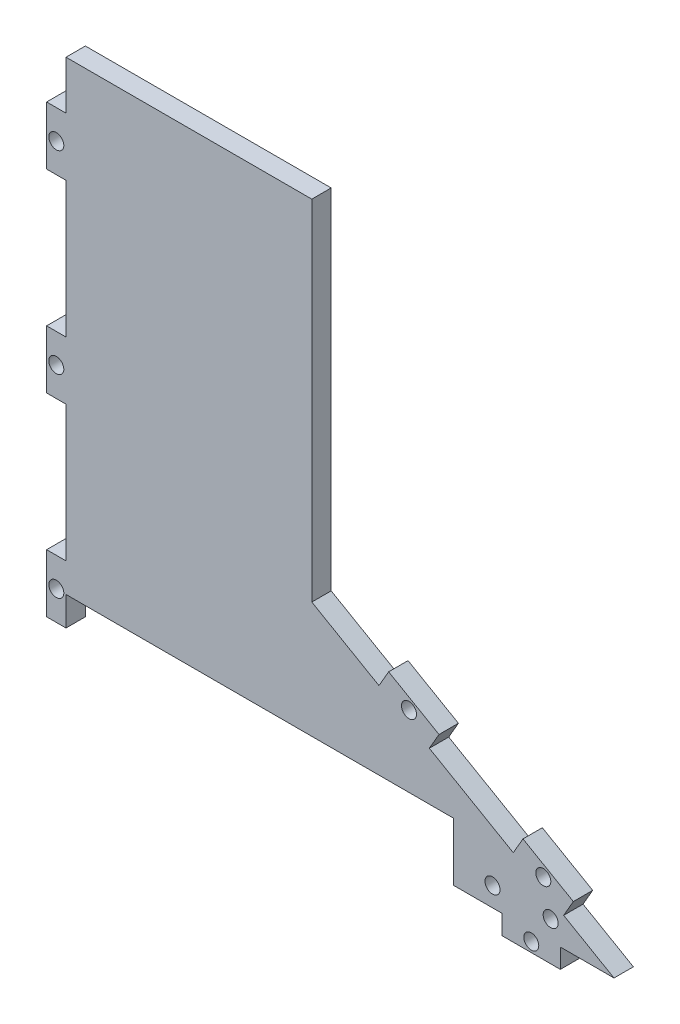
SolidWorks part; units mm, degrees
ref_plane "Front Plane" through (0, 0, 0) normal (0, 0, 1) x (1, 0, 0)
ref_plane "Top Plane" through (0, 0, 0) normal (0, 1, 0) x (1, 0, 0)
ref_plane "Right Plane" through (0, 0, 0) normal (1, 0, 0) x (0, 0, -1)
sketch "Sketch1" plane through (0, 0, 0) normal (0, 0, 1) x (1, 0, 0)
  line L0 (86.8648, 57.15) -> (185.8515, 0)
  line L1 (0, 0) -> (86.8648, 0)
  line L2 (0, 0) -> (0, 57.15)
  line L3 (0, 57.15) -> (86.8648, 57.15)
  line L5 (185.8515, 0) -> (86.8648, 0)
  dimension "D1" = 86.8648
  dimension "D2" = 30
  dimension "D3" = 114.3
extrude "Boss-Extrude1" add sketch "Sketch1" along normal blind 6.35
sketch "Sketch2" plane through (0, 0, 6.35) normal (0, 0, 1) x (1, 0, 0)
  line L0 (0, 0) -> (185.8515, 0) construction
  line L1 (6.35, 0) -> (133.35, 0)
  line L2 (6.35, 0) -> (6.35, 19.05)
  line L3 (6.35, 19.05) -> (133.35, 19.05)
  line L4 (133.35, 0) -> (133.35, 19.05)
  line L5 (0, 57.15) -> (0, 0) construction
  dimension "D1" = 127
  dimension "D2" = 19.05
  dimension "D3" = 6.35
extrude "Cut-Extrude1" cut sketch "Sketch2" against normal through all
sketch "Sketch3" plane through (0, 0, 6.35) normal (0, 0, 1) x (1, 0, 0)
  line L0 (86.8648, 57.15) -> (0, 57.15) construction
  line L1 (0, 57.15) -> (86.8648, 57.15)
  line L2 (0, 57.15) -> (0, 171.45)
  line L3 (0, 171.45) -> (86.8648, 171.45)
  line L4 (86.8648, 57.15) -> (86.8648, 171.45)
  line L5 (0, 57.15) -> (0, 0) construction
  dimension "D1" = 114.3
  dimension "D2" = 86.8648
extrude "Boss-Extrude2" add sketch "Sketch3" against normal blind 6.35
sketch "Sketch4" plane through (0, 0, 6.35) normal (0, 0, 1) x (1, 0, 0)
  line L0 (6.35, 19.05) -> (6.35, 0) construction
  line L1 (0, 0) -> (6.35, 0)
  line L2 (0, 0) -> (0, 9.525)
  line L3 (0, 9.525) -> (6.35, 9.525)
  line L4 (6.35, 0) -> (6.35, 9.525)
  line L5 (0, 171.45) -> (0, 0) construction
  line L6 (0, 28.575) -> (6.35, 28.575)
  line L7 (0, 28.575) -> (0, 73.025)
  line L8 (0, 73.025) -> (6.35, 73.025)
  line L9 (6.35, 28.575) -> (6.35, 73.025)
  line L11 (0, 92.075) -> (6.35, 92.075)
  line L12 (0, 92.075) -> (0, 136.525)
  line L13 (0, 136.525) -> (6.35, 136.525)
  line L14 (6.35, 92.075) -> (6.35, 136.525)
  line L15 (0, 171.45) -> (6.35, 171.45)
  line L16 (0, 171.45) -> (0, 155.575)
  line L17 (0, 155.575) -> (6.35, 155.575)
  line L18 (6.35, 171.45) -> (6.35, 155.575)
  dimension "D1" = 9.525
  dimension "D2" = 19.05
  dimension "D3" = 44.45
  dimension "D4" = 6.35
  dimension "D5" = 19.05
  dimension "D6" = 44.45
  dimension "D7" = 6.35
  dimension "D8" = 19.05
  dimension "D9" = 6.35
extrude "Cut-Extrude2" cut sketch "Sketch4" against normal through all
sketch "Sketch5" plane through (0, 0, 6.35) normal (0, 0, 1) x (1, 0, 0)
  line L0 (133.35, 0) -> (185.8515, 0) construction
  line L1 (149.225, 0) -> (168.275, 0)
  line L2 (149.225, 0) -> (149.225, -6.35)
  line L3 (149.225, -6.35) -> (168.275, -6.35)
  line L4 (168.275, 0) -> (168.275, -6.35)
  line L5 (6.35, 28.575) -> (6.35, 73.025) construction
  dimension "D1" = 19.05
  dimension "D2" = 6.35
  dimension "D3" = 142.875
extrude "Boss-Extrude3" add sketch "Sketch5" against normal blind 6.35
sketch "Sketch6" plane through (0, 0, 6.35) normal (0, 0, 1) x (1, 0, 0)
  line L0 (185.8515, 0) -> (86.8648, 57.15) construction
  line L1 (108.8618, 44.45) -> (125.3596, 34.925)
  line L2 (108.8618, 44.45) -> (112.0368, 49.9493)
  line L3 (112.0368, 49.9493) -> (128.5346, 40.4243)
  line L4 (125.3596, 34.925) -> (128.5346, 40.4243)
  dimension "D1" = 19.05
  dimension "D2" = 6.35
  dimension "D3" = 25.4
extrude "Boss-Extrude4" add sketch "Sketch6" against normal blind 6.35
pattern_linear "LPattern1" count 2 spacing 50.8 along (0.866, -0.5, 0) of "Boss-Extrude4"
sketch "Sketch8" [suppressed] plane through (0, 0, 6.35) normal (0, 0, 1) x (1, 0, 0)
  line L0 (0, 0) -> (185.8515, 0) construction
  line L1 (34.925, 0) -> (53.975, 0)
  line L2 (34.925, 0) -> (34.925, -6.35)
  line L3 (34.925, -6.35) -> (53.975, -6.35)
  line L4 (53.975, 0) -> (53.975, -6.35)
  dimension "D1" = 6.35
  dimension "D2" = 19.05
  dimension "D3" = 34.925
extrude "Boss-Extrude6" [suppressed] add sketch "Sketch8" against normal blind 6.35
pattern_linear "LPattern2" [suppressed] count 3 spacing 57.15
sketch "Sketch9" [suppressed] plane through (0, 0, 6.35) normal (0, 0, 1) x (1, 0, 0)
  line L0 (185.8515, 0) -> (86.8648, 57.15) construction
  line L1 (108.8618, 44.45) -> (125.3596, 34.925)
  line L2 (108.8618, 44.45) -> (112.0368, 49.9493)
  line L3 (112.0368, 49.9493) -> (128.5346, 40.4243)
  line L4 (125.3596, 34.925) -> (128.5346, 40.4243)
  dimension "D1" = 6.35
  dimension "D2" = 19.05
  dimension "D3" = 25.4
extrude "Boss-Extrude7" [suppressed] add sketch "Sketch9" against normal blind 6.35
pattern_linear "LPattern3" [suppressed] count 2 spacing 50.8
sketch "Sketch10" [suppressed] plane through (0, 0, 6.35) normal (0, 0, 1) x (1, 0, 0)
  line L1 (0, 57.15) -> (6.35, 57.15)
  line L2 (0, 57.15) -> (0, 28.575)
  line L3 (0, 28.575) -> (6.35, 28.575)
  line L4 (6.35, 57.15) -> (6.35, 28.575)
  line L5 (0, 0) -> (6.35, 0)
  line L6 (0, 0) -> (0, 9.525)
  line L7 (0, 9.525) -> (6.35, 9.525)
  line L8 (6.35, 0) -> (6.35, 9.525)
  dimension "D1" = 6.35
  dimension "D2" = 6.35
  dimension "D3" = 9.525
  dimension "D4" = 19.05
extrude "Cut-Extrude3" [suppressed] cut sketch "Sketch10" against normal through all
hole_wizard "#10 (0.1935) Diameter Hole1" positions "Sketch12" profile "Sketch11" hole size "#10" standard "ANSI Inch" end condition through all
sketch "Sketch12" plane through (0, 0, 6.35) normal (0, 0, 1) x (1, 0, 0)
  line L0 (3.175, 155.575) -> (3.175, 136.525) construction
  line L1 (0, 155.575) -> (6.35, 155.575) construction
  line L2 (6.35, 136.525) -> (0, 136.525) construction
  point P0 (3.175, 146.05)
  point P19 (3.175, 82.55)
  point P20 (3.175, 19.05)
  dimension "D1" = 3
sketch "Sketch11" plane through (3.175, 146.05, 6.35) normal (1, 0, 0) x (0, -1, 0)
  line L0 (0, 0) -> (0, 6.35)
  line L1 (0, 6.35) -> (2.4574, 6.35)
  line L2 (2.4574, 6.35) -> (2.4574, 0)
  line L5 (2.4574, 0) -> (0, 0)
  line L11 (0, -6.35) -> (0, 107.95) construction
  dimension "Thru Hole Dia." = 4.9149
  dimension "Thru Hole Depth" = 6.35
hole_wizard "#10 (0.1935) Diameter Hole2" positions "Sketch14" profile "Sketch13" hole size "#10" standard "ANSI Inch" end condition through all
sketch "Sketch14" plane through (0, 0, 6.35) normal (0, 0, 1) x (1, 0, 0)
  line L0 (110.4493, 47.1996) -> (126.9471, 37.6746) construction
  line L1 (112.0368, 49.9493) -> (108.8618, 44.45) construction
  line L2 (125.3596, 34.925) -> (128.5346, 40.4243) construction
  line L3 (149.225, -3.175) -> (168.275, -3.175) construction
  line L4 (149.225, 0) -> (149.225, -6.35) construction
  line L5 (168.275, -6.35) -> (168.275, 0) construction
  point P0 (118.6982, 42.4371)
  point P18 (162.6923, 17.0371)
  point P19 (158.75, -3.175)
  dimension "D1" = 2
sketch "Sketch13" plane through (118.6982, 42.4371, 6.35) normal (1, 0, 0) x (0, -1, 0)
  line L0 (0, 0) -> (0, 6.35)
  line L1 (0, 6.35) -> (2.4574, 6.35)
  line L2 (2.4574, 6.35) -> (2.4574, 0)
  line L5 (2.4574, 0) -> (0, 0)
  line L11 (0, -6.35) -> (0, 107.95) construction
  dimension "Thru Hole Dia." = 4.9149
  dimension "Thru Hole Depth" = 6.35
hole_wizard "#10 (0.1935) Diameter Hole3" positions "Sketch16" profile "Sketch15" hole size "#10" standard "ANSI Inch" end condition through all
sketch "Sketch16" plane through (0, 0, 6.35) normal (0, 0, 1) x (1, 0, 0)
  line L3 (146.05, 6.35) -> (174.853, 6.35) construction
  line L4 (185.8515, 0) -> (169.3537, 9.525) construction
  line L5 (168.275, 0) -> (185.8515, 0) construction
  point P0 (146.05, 6.35)
  point P2 (165.1, 6.35)
  dimension "D1" = 19.05
  dimension "D2" = 6.35
  dimension "D3" = 9.753
sketch "Sketch15" plane through (146.05, 6.35, 6.35) normal (1, 0, 0) x (0, -1, 0)
  line L0 (0, 0) -> (0, 6.35)
  line L1 (0, 6.35) -> (2.4574, 6.35)
  line L2 (2.4574, 6.35) -> (2.4574, 0)
  line L5 (2.4574, 0) -> (0, 0)
  line L11 (0, -6.35) -> (0, 107.95) construction
  dimension "Thru Hole Dia." = 4.9149
  dimension "Thru Hole Depth" = 6.35
hole_wizard "#10 (0.1935) Diameter Hole4" [suppressed] positions "Sketch18" profile "Sketch17" hole size "#10" standard "ANSI Inch"
sketch "Sketch18" [suppressed] plane through (0, 0, 6.35) normal (0, 0, 1) x (1, 0, 0)
  line L0 (34.925, -3.175) -> (53.975, -3.175) construction
  line L1 (34.925, 0) -> (34.925, -6.35) construction
  line L2 (53.975, -6.35) -> (53.975, 0) construction
  line L3 (110.4493, 47.1996) -> (126.9471, 37.6746) construction
  line L4 (112.0368, 49.9493) -> (108.8618, 44.45) construction
  line L5 (125.3596, 34.925) -> (128.5346, 40.4243) construction
  line L6 (3.175, 28.575) -> (3.175, 9.525) construction
  line L7 (0, 28.575) -> (6.35, 28.575) construction
  line L8 (6.35, 9.525) -> (0, 9.525) construction
  point P0 (44.45, -3.175)
  point P19 (101.6, -3.175)
  point P20 (158.75, -3.175)
  point P21 (118.6982, 42.4371)
  point P39 (162.6923, 17.0371)
  point P40 (3.175, 19.05)
  dimension "D1" = 3
  dimension "D2" = 2
sketch "Sketch17" plane through (44.45, -3.175, 6.35) normal (1, 0, 0) x (0, -1, 0)
  line L0 (0, 0) -> (0, 6.35)
  line L1 (0, 6.35) -> (2.4574, 6.35)
  line L2 (2.4574, 6.35) -> (2.4574, 0)
  line L5 (2.4574, 0) -> (0, 0)
  line L11 (0, -6.35) -> (0, 107.95) construction
  dimension "Thru Hole Dia." = 4.9149
  dimension "Thru Hole Depth" = 6.35
